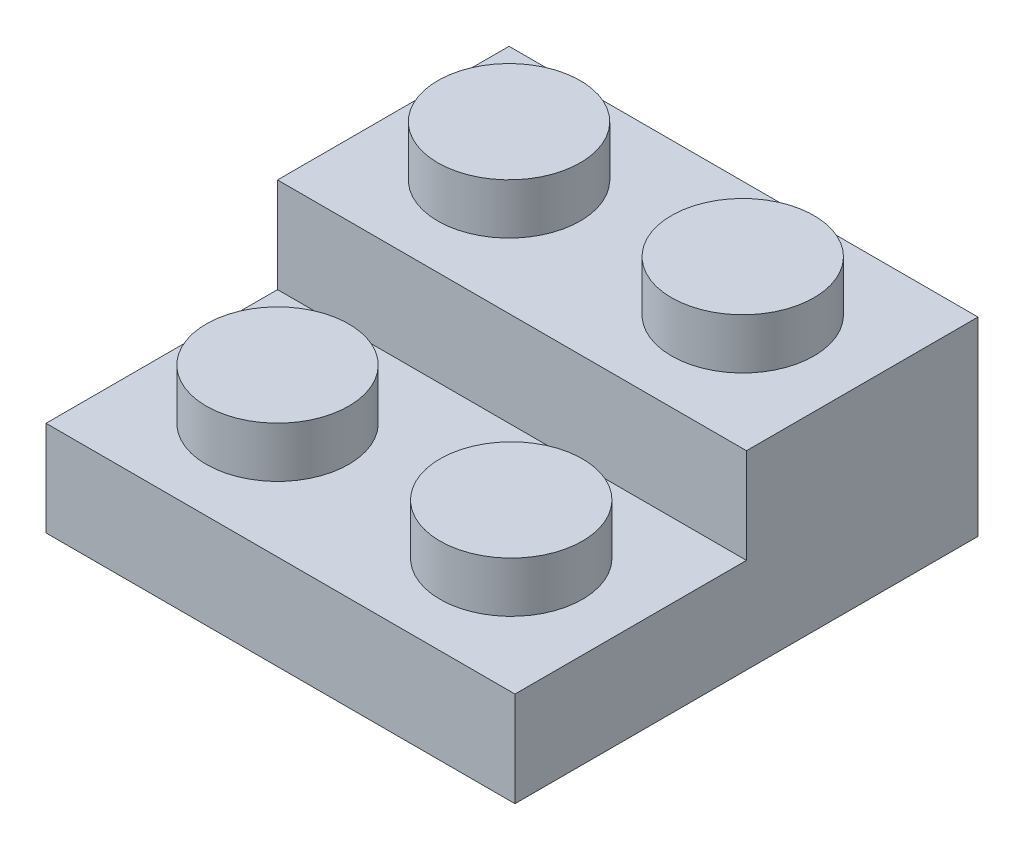
SolidWorks part; units mm, degrees
ref_plane "Спереди" through (0, 0, 0) normal (0, 0, 1) x (1, 0, 0)
ref_plane "Сверху" through (0, 0, 0) normal (0, 1, 0) x (1, 0, 0)
ref_plane "Справа" through (0, 0, 0) normal (1, 0, 0) x (0, 0, -1)
sketch "Эскиз1" plane through (0, 0, 0) normal (0, 1, 0) x (1, 0, 0)
  line L5 (7.9, -7.8) -> (-7.9, -7.8)
  line L6 (7.9, -7.8) -> (7.9, 7.8)
  line L7 (7.9, 7.8) -> (-7.9, 7.8)
  line L8 (-7.9, -7.8) -> (-7.9, 7.8)
  line L9 (7.9, -7.8) -> (-7.9, 7.8) construction
  line L10 (7.9, 7.8) -> (-7.9, -7.8) construction
  point P0 (0, 0)
  dimension "D1" = 15.8
  dimension "D2" = 15.6
extrude "Бобышка-Вытянуть2" add sketch "Эскиз1" along normal blind 6.4
sketch "Эскиз2" plane through (0, 6.4, 0) normal (0, 1, 0) x (1, 0, 0)
  line L0 (0, 0) -> (-7.9, 0)
  line L1 (-7.9, 7.8) -> (-7.9, -7.8) construction
  line L2 (0, 0) -> (7.9, 0)
  line L3 (7.9, -7.8) -> (7.9, 7.8) construction
  line L5 (-7.9, 0) -> (7.9, 0)
  line L6 (-7.9, 0) -> (-7.9, -7.8)
  line L7 (-7.9, -7.8) -> (7.9, -7.8)
  line L8 (7.9, 0) -> (7.9, -7.8)
  line M1 (-7.9, 7.8) -> (-7.9, -7.8)
  line M2 (-7.9, -7.8) -> (7.9, -7.8)
  line M3 (7.9, -7.8) -> (7.9, 7.8)
extrude "Вырез-Вытянуть1" cut sketch "Эскиз2" against normal blind 3.2 contours L2 L0 M1 M2 M3
sketch "Эскиз3" plane through (0, 3.2, 0) normal (0, 1, 0) x (1, 0, 0)
  line L0 (-7.9, 0) -> (-7.9, -7.8) construction
  line L1 (-7.9, -7.8) -> (7.9, -7.8) construction
  circle A0 centre (-4, -3.9) radius 2.4
  circle A1 centre (3.874, -3.9) radius 2.4
  dimension "D1" = 3.9
  dimension "D3" = 2
  dimension "D2" = 3.9
extrude "Бобышка-Вытянуть3" add sketch "Эскиз3" along normal blind 1.7
sketch "Эскиз4" plane through (0, 6.4, 0) normal (0, 1, 0) x (1, 0, 0)
  line L0 (7.9, 7.8) -> (-7.9, 7.8) construction
  line L1 (-7.9, 7.8) -> (-7.9, 0) construction
  circle A0 centre (-4, 3.9) radius 2.4
  circle A1 centre (3.874, 3.9) radius 2.4
  dimension "D1" = 3.9
  dimension "D2" = 3.9
  dimension "D3" = 2
extrude "Бобышка-Вытянуть4" add sketch "Эскиз4" along normal blind 1.7
sketch "Эскиз5" plane through (0, 0, 0) normal (0, -1, 0) x (1, 0, 0)
  line L0 (-7.9, 7.8) -> (7.9, -7.8)
  line L1 (7.9, 7.8) -> (-7.9, -7.8)
  line L2 (0, 0) -> (-7.9, 0)
  line L3 (-7.9, -7.8) -> (-7.9, 7.8) construction
  line L4 (0, 0) -> (7.9, 0)
  line L5 (7.9, 7.8) -> (7.9, -7.8) construction
  line L6 (-7.9, 0) -> (7.9, -7.8)
  line L7 (-7.9, -7.8) -> (7.9, 0)
  line L8 (-7.9, 0) -> (7.9, 7.8)
  line L9 (-7.9, 7.8) -> (7.9, 0)
  circle A0 centre (0, 3.9) radius 2.5
extrude "Вырез-Вытянуть2" cut sketch "Эскиз5" against normal blind 1.8 contours L8 A0 L9 | L9 A0 L8 | L8 A0 L9 | L9 A0 L8
sketch "Эскиз6" plane through (0, 0, 0) normal (0, -1, 0) x (1, 0, 0)
  circle A0 centre (0, -3.9345) radius 2.5
extrude "Вырез-Вытянуть3" cut sketch "Эскиз6" against normal blind 1.8 contours A0
